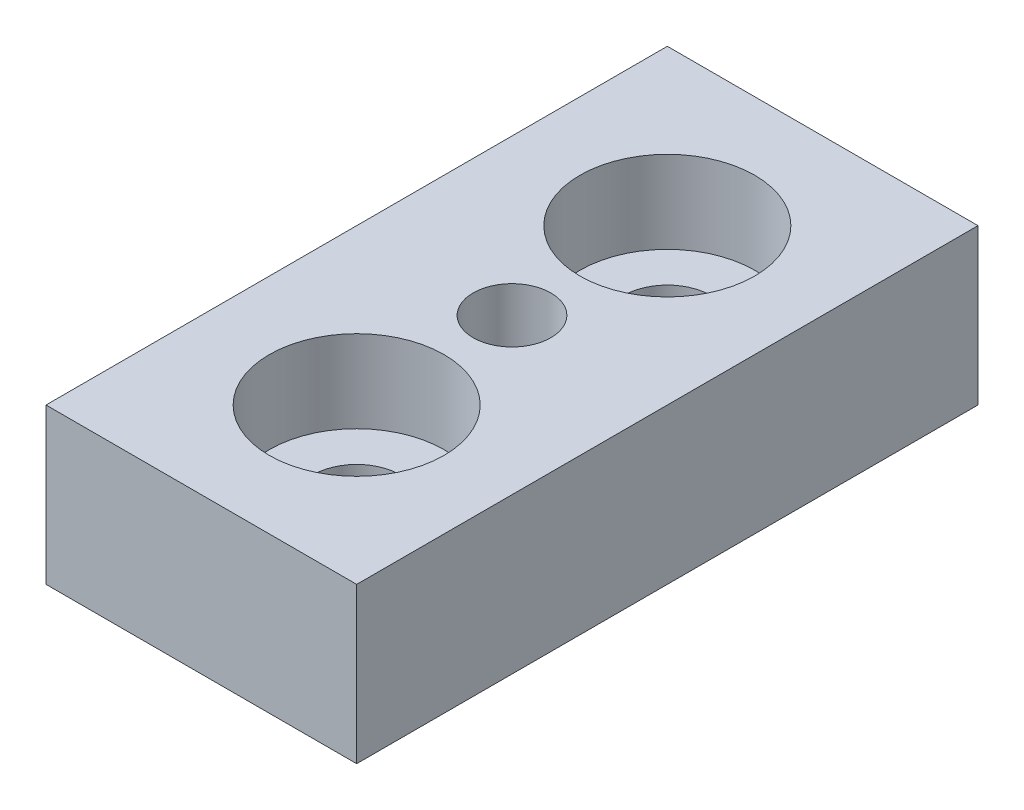
SolidWorks part; units mm, degrees
ref_plane "Front" through (0, 0, 0) normal (0, 0, 1) x (1, 0, 0)
ref_plane "Top" through (0, 0, 0) normal (0, 1, 0) x (1, 0, 0)
ref_plane "Right" through (0, 0, 0) normal (1, 0, 0) x (0, 0, -1)
sketch "Sketch1" plane through (0, 0, 0) normal (0, 1, 0) x (1, 0, 0)
  line L0 (0, 25.4) -> (0, -25.4) construction
  line L1 (-12.7, 25.4) -> (12.7, 25.4)
  line L2 (-12.7, 25.4) -> (-12.7, -25.4)
  line L3 (-12.7, -25.4) -> (12.7, -25.4)
  line L4 (12.7, 25.4) -> (12.7, -25.4)
  dimension "D1" = 25.4
  dimension "D2" = 50.8
extrude "Extrude1" add sketch "Sketch1" along normal blind 12.7
hole_wizard "1/4 (0.25) Diameter Hole1" positions "Sketch3" profile "Sketch4" hole size "1/4" standard "Ansi Inch" end condition through all
sketch "Sketch3" plane through (0, 12.7, 0) normal (0, 1, 0) x (-1, 0, 0)
  line L0 (0, -25.4) -> (0, 25.4) construction
  line L1 (-12.7, -25.4) -> (12.7, -25.4) construction
  line L2 (12.7, 25.4) -> (-12.7, 25.4) construction
  point P0 (0, 0)
sketch "Sketch4" plane through (0, 12.7, 0) normal (1, 0, 0) x (0, 0, 1)
  line L0 (0, 0) -> (0, 12.7)
  line L1 (0, 12.7) -> (3.175, 12.7)
  line L2 (3.175, 12.7) -> (3.175, 0)
  line L5 (3.175, 0) -> (0, 0)
  line L11 (0, -6.35) -> (0, 107.95) construction
  dimension "Thru Hole Dia." = 6.35
  dimension "Thru Hole Depth" = 12.7
hole_wizard "CBORE for 1/4 Binding Head Machine Screw1" positions "Sketch6" profile "Sketch5" counterbore size "1/4" standard "Ansi Inch" end condition through all
sketch "Sketch6" plane through (0, 12.7, 0) normal (0, 1, 0) x (-1, 0, 0)
  line L0 (0, -12.7) -> (0, 12.7) construction
  point P0 (0, -12.7)
  point P1 (0, 12.7)
  dimension "D1" = 25.4
sketch "Sketch5" plane through (0, 12.7, -12.7) normal (1, 0, 0) x (0, 0, 1)
  line L0 (0, 0) -> (0, 12.7)
  line L1 (0, 12.7) -> (3.5712, 12.7)
  line L3 (3.5712, 12.7) -> (3.5712, 6.731)
  line L4 (3.5712, 6.731) -> (7.1437, 6.731)
  line L5 (7.1437, 6.731) -> (7.1437, 0)
  line L7 (7.1437, 0) -> (0, 0)
  line L11 (0, -6.35) -> (0, 107.95) construction
  dimension "Thru Hole Dia." = 7.1425
  dimension "Thru Hole Depth" = 12.7
  dimension "C'Bore Dia." = 14.2875
  dimension "C'Bore Depth" = 6.731
